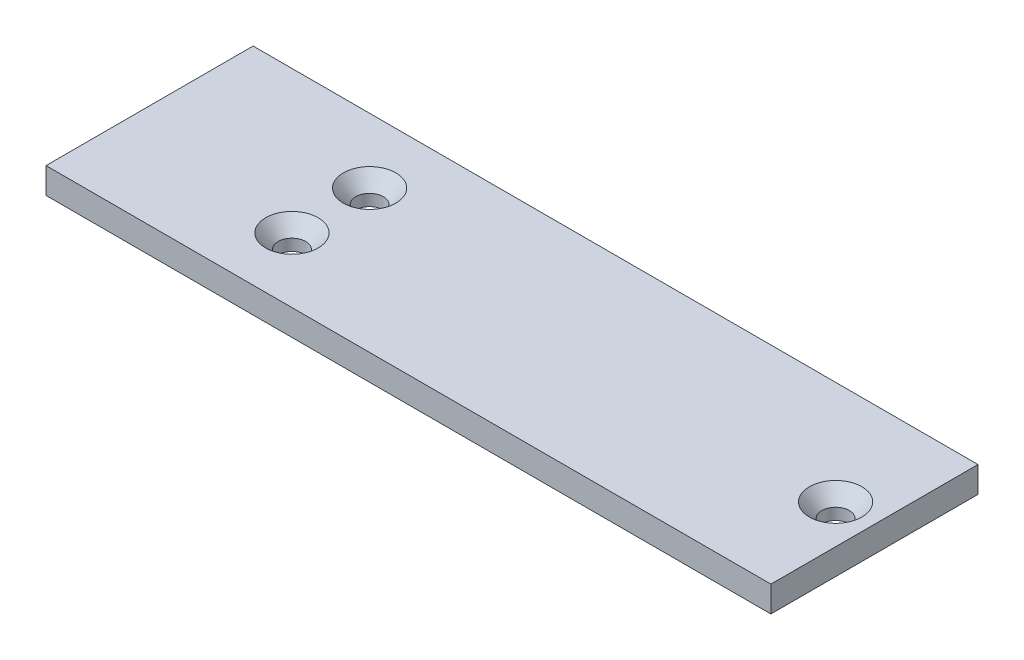
SolidWorks part; units mm, degrees
material "6061 Alloy"
ref_plane "Front Plane" through (0, 0, 0) normal (0, 0, 1) x (1, 0, 0)
ref_plane "Top Plane" through (0, 0, 0) normal (0, 1, 0) x (1, 0, 0)
ref_plane "Right Plane" through (0, 0, 0) normal (1, 0, 0) x (0, 0, -1)
sketch "Sketch1" plane through (0, 0, 0) normal (0, 1, 0) x (1, 0, 0)
  line L1 (88.9, -25.4) -> (-88.9, -25.4)
  line L2 (88.9, -25.4) -> (88.9, 25.4)
  line L3 (88.9, 25.4) -> (-88.9, 25.4)
  line L4 (-88.9, -25.4) -> (-88.9, 25.4)
  line L5 (88.9, -25.4) -> (-88.9, 25.4) construction
  line L6 (88.9, 25.4) -> (-88.9, -25.4) construction
  point P0 (0, 0)
  dimension "D1" = 177.8
  dimension "D2" = 50.8
extrude "Boss-Extrude1" add sketch "Sketch1" along normal mid plane 6.35
hole_wizard "CSK for 1/4 Flat Head Machine Screw1" positions "Sketch2" profile "Sketch3" countersink size "1/4" standard "ANSI Inch"
sketch "Sketch2" plane through (0, 3.175, 0) normal (0, 1, 0) x (1, 0, 0)
  line L0 (-88.9, -25.4) -> (88.9, -25.4) construction
  line L1 (-44.45, -9.525) -> (-44.45, 9.525) construction
  line L3 (88.9, 25.4) -> (-88.9, 25.4) construction
  line L4 (88.9, -25.4) -> (88.9, 25.4) construction
  point P0 (79.375, 0)
  point P2 (-44.45, 9.525)
  point P4 (-44.45, -9.525)
  dimension "D1" = 25.4
  dimension "D2" = 15.875
  dimension "D3" = 15.875
  dimension "D4" = 9.525
  dimension "D5" = 133.35
sketch "Sketch3" plane through (79.375, 3.175, 0) normal (1, 0, 0) x (0, 0, 1)
  line L0 (0, 0) -> (0, 21.0798)
  line L1 (0, 21.0798) -> (3.3782, 19.05)
  line L2 (3.3782, 19.05) -> (3.3782, 3.5209)
  line L3 (3.3782, 3.5209) -> (6.4389, 0)
  line L5 (6.4389, 0) -> (0, 0)
  line L6 (-3.3782, 3.5209) -> (-6.4389, 0) construction
  line L10 (0, 21.0798) -> (-3.3782, 19.05) construction
  line L11 (0, -6.35) -> (0, 107.95) construction
  dimension "Hole Dia." = 6.7564
  dimension "Hole Depth" = 19.05
  dimension "Near C'Sink Dia." = 12.8778
  dimension "Near C'Sink Angle" = 82
  dimension "Drill Angle" = 118
